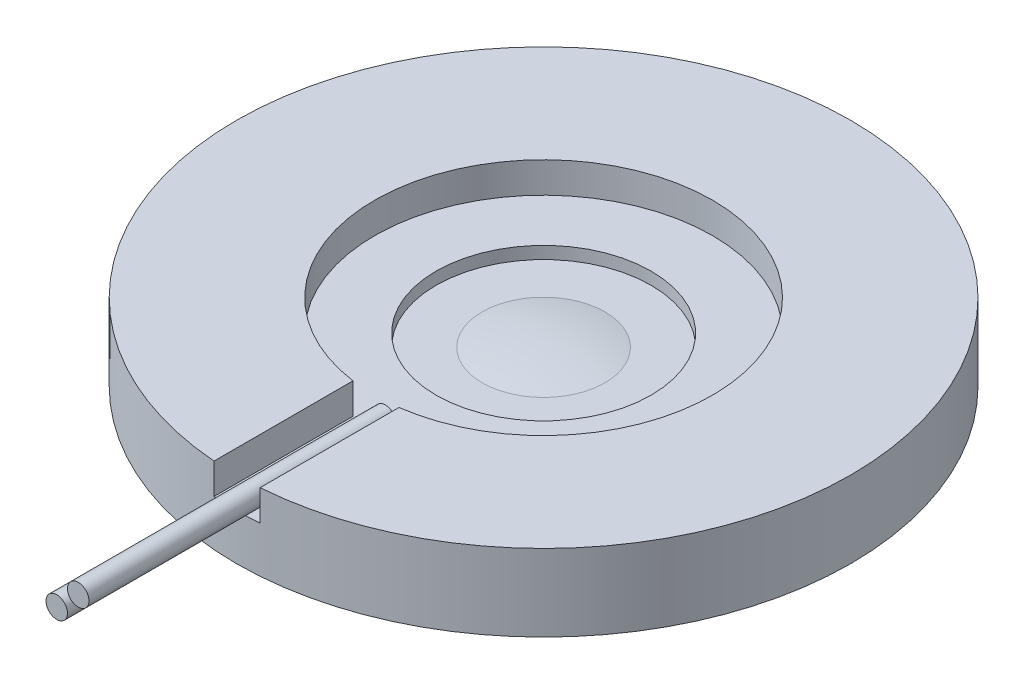
SolidWorks part; units mm, degrees
ref_plane "Płaszczyzna przednia" through (0, 0, 0) normal (0, 0, 1) x (1, 0, 0)
ref_plane "Płaszczyzna górna" through (0, 0, 0) normal (0, 1, 0) x (1, 0, 0)
ref_plane "Płaszczyzna prawa" through (0, 0, 0) normal (1, 0, 0) x (0, 0, -1)
sketch "Sketch2" plane through (0, 0, 0) normal (0, 0, 1) x (1, 0, 0)
  line L0 (-1.99, 0) -> (-6, 0)
  line L1 (-6, 0) -> (-6, -1)
  line L2 (-6, -1) -> (-10, -1)
  line L3 (-10, -1) -> (-10, 1.5)
  line L4 (-10, 1.5) -> (-5.5, 1.5)
  line L5 (-5.5, 1.5) -> (-5.5, 0.5)
  line L6 (-5.5, 0.5) -> (-3.5, 0.5)
  line L7 (-3.5, 0.5) -> (-3.5, 0.1)
  line L8 (-3.5, 0.1) -> (-2, 0.1)
  line L9 (0, -1.2162) -> (0, 4.5274) construction
  line L10 (0, 0.2) -> (0, 0.3)
  arc A0 (-1.99, 0) -> (0, 0.2) centre (0, -9.8) cw
  arc A1 (-2, 0.1) -> (0, 0.3) centre (0, -9.8) cw
  dimension "D1" = 10
  dimension "D2" = 4
  dimension "D3" = 2.5
  dimension "D4" = 3.5
  dimension "D5" = 5.5
  dimension "D6" = 1
  dimension "D7" = 0.1
  dimension "D8" = 0.1
  dimension "D9" = 0.2
  dimension "D10" = 1
  dimension "D11" = 2
revolve "Revolve1" add sketch "Sketch2" angle 360 about L9
sketch "Sketch5" plane through (0, 1.5, 0) normal (0, 1, 0) x (1, 0, 0)
  line L1 (-0.7579, -10.5892) -> (0.7421, -10.5892)
  line L2 (-0.7579, -10.5892) -> (-0.7579, -4.2273)
  line L3 (-0.7579, -4.2273) -> (0.7421, -4.2273)
  line L4 (0.7421, -10.5892) -> (0.7421, -4.2273)
  line L5 (-0.7579, -10.5892) -> (0.7421, -4.2273) construction
  line L6 (-0.7579, -4.2273) -> (0.7421, -10.5892) construction
  circle A0 centre (0, 0) radius 10 construction
  circle A1 centre (0, 0) radius 5.5 construction
  circle A2 centre (0, 0) radius 10 construction
  circle A3 centre (0, 0) radius 5.5 construction
  point P6 (-0.0079, -7.4083)
  dimension "D1" = 1.5
extrude "Cut-Extrude1" cut sketch "Sketch5" against normal up to surface (1 mm away) up to face at (0, 0.5, -5.5)
sketch "Sketch3" plane through (0, 0, 0) normal (0, 0, 1) x (1, 0, 0)
  line L0 (0, 0) -> (0, 3.0301) construction
  line L1 (1.2569, 0) -> (-2.3221, 0) construction
  line L2 (-1.647, 0.7) -> (1.932, 0.7) construction
  circle A0 centre (-0.35, 0.35) radius 0.35
  circle A1 centre (0.35, 1.05) radius 0.35
  dimension "D1" = 0.7
extrude "Boss-Extrude1" add sketch "Sketch3" along normal blind 10 from offset 5.5
